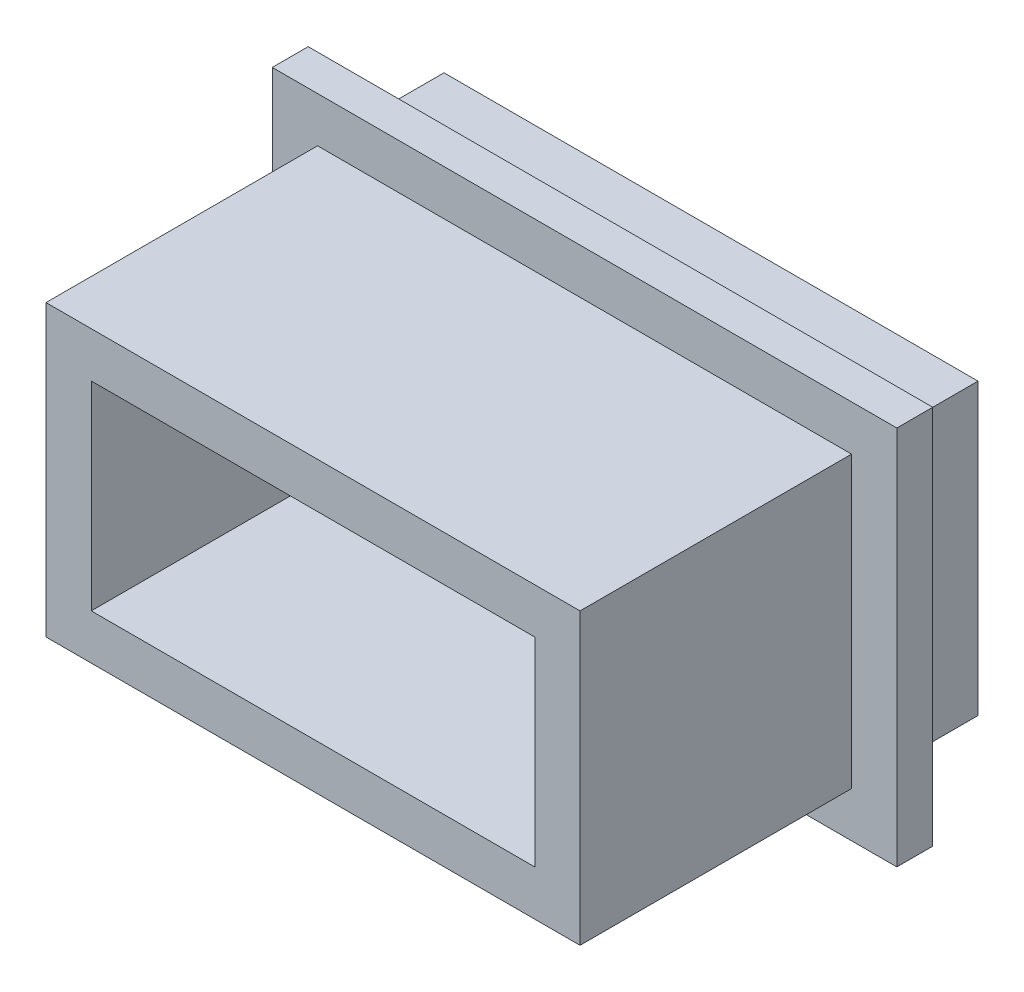
SolidWorks part; units mm, degrees
ref_plane "Front Plane" through (0, 0, 0) normal (0, 0, 1) x (1, 0, 0)
ref_plane "Top Plane" through (0, 0, 0) normal (0, 1, 0) x (1, 0, 0)
ref_plane "Right Plane" through (0, 0, 0) normal (1, 0, 0) x (0, 0, -1)
sketch "Sketch1" plane through (0, 0, 0) normal (0, 0, 1) x (1, 0, 0)
  line L4 (2.45, 4.3) -> (2.45, 6.5)
  line L5 (2.45, 6.5) -> (-2.45, 6.5)
  line L6 (-2.45, 6.5) -> (-2.45, 4.3)
  line L7 (-2.45, 4.3) -> (2.45, 4.3)
  line L8 (2.95, 3.8) -> (2.95, 7)
  line L9 (2.95, 7) -> (-2.95, 7)
  line L10 (-2.95, 7) -> (-2.95, 3.8)
  line L11 (-2.95, 3.8) -> (2.95, 3.8)
  dimension "D1" = 0.5
extrude "Boss-Extrude1" add sketch "Sketch1" along normal up to surface (1 mm away)
sketch "Sketch2" plane through (0, 0, 1) normal (0, 0, 1) x (1, 0, 0)
  line L4 (2.45, 6.5) -> (2.45, 4.3) construction
  line L5 (2.45, 4.3) -> (-2.45, 4.3) construction
  line L6 (-2.45, 4.3) -> (-2.45, 6.5) construction
  line L7 (-2.45, 6.5) -> (2.45, 6.5) construction
  line L8 (3.45, 3.3) -> (3.45, 7.5)
  line L9 (3.45, 7.5) -> (-3.45, 7.5)
  line L10 (-3.45, 7.5) -> (-3.45, 3.3)
  line L11 (-3.45, 3.3) -> (3.45, 3.3)
  line L12 (3.45, 3.3) -> (3.45, 7.5)
  line L13 (3.45, 7.5) -> (-3.45, 7.5)
  line L14 (-3.45, 7.5) -> (-3.45, 3.3)
  line L15 (-3.45, 3.3) -> (3.45, 3.3)
  line L16 (2.45, 6.5) -> (2.45, 4.3)
  line L17 (2.45, 4.3) -> (-2.45, 4.3)
  line L18 (-2.45, 4.3) -> (-2.45, 6.5)
  line L19 (-2.45, 6.5) -> (2.45, 6.5)
  dimension "D1" = 0.5
extrude "Boss-Extrude2" add sketch "Sketch2" along normal blind 0.3969
sketch "Sketch3" plane through (0, 0, 1.3969) normal (0, 0, 1) x (1, 0, 0)
  line L4 (-2.45, 4.3) -> (2.45, 4.3) construction
  line L5 (-2.45, 4.3) -> (2.45, 4.3)
  line L6 (2.45, 4.3) -> (2.45, 6.5) construction
  line L7 (2.45, 6.5) -> (-2.45, 6.5) construction
  line L8 (2.95, 3.8) -> (2.95, 7)
  line L9 (2.95, 7) -> (-2.95, 7)
  line L10 (-2.95, 7) -> (-2.95, 3.8)
  line L11 (-2.95, 3.8) -> (2.95, 3.8)
  line L12 (-2.45, 6.5) -> (-2.45, 4.3) construction
  line L13 (2.45, 4.3) -> (2.45, 6.5)
  line L14 (2.45, 6.5) -> (-2.45, 6.5)
  line L15 (-2.45, 6.5) -> (-2.45, 4.3)
extrude "Boss-Extrude3" add sketch "Sketch3" along normal blind 3
